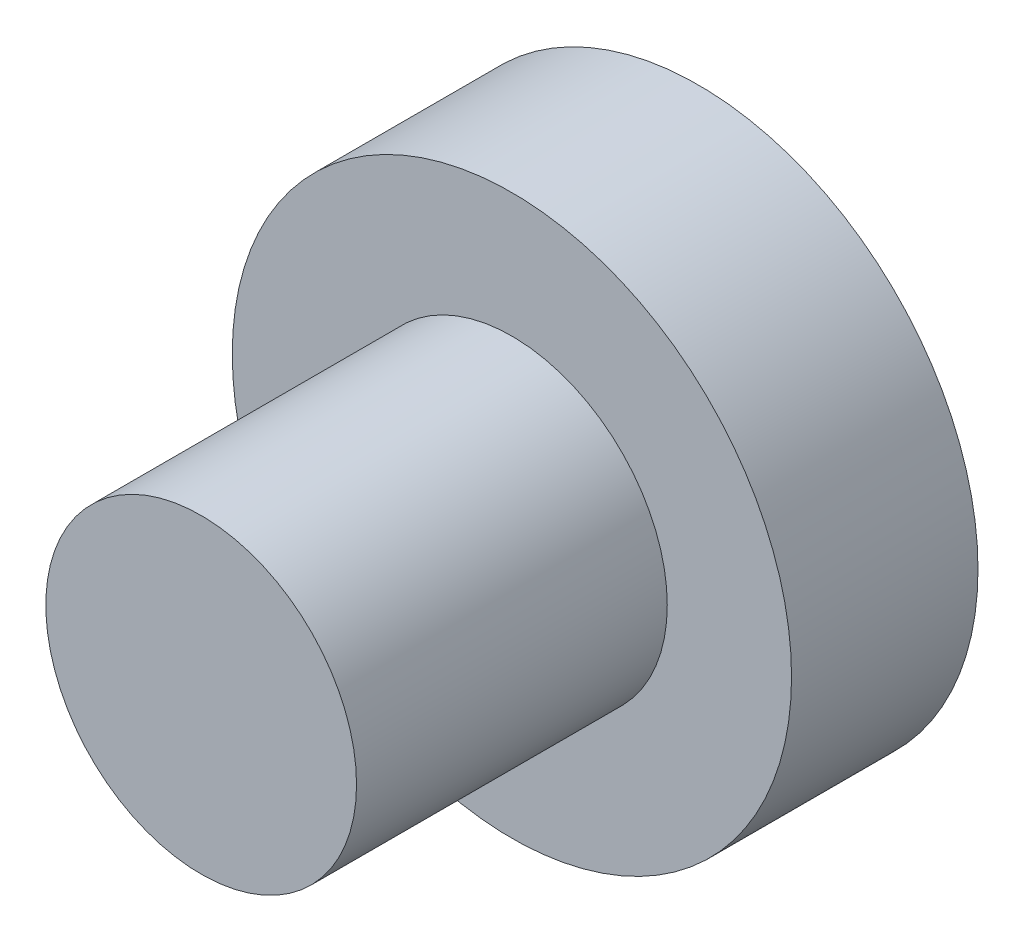
SolidWorks part; units mm, degrees
ref_plane "Front Plane" through (0, 0, 0) normal (0, 0, 1) x (1, 0, 0)
ref_plane "Top Plane" through (0, 0, 0) normal (0, 1, 0) x (1, 0, 0)
ref_plane "Right Plane" through (0, 0, 0) normal (1, 0, 0) x (0, 0, -1)
sketch "Sketch2" plane through (0, 0, 0) normal (0, 0, 1) x (1, 0, 0)
  circle A0 centre (0, 0) radius 2.5
  circle A1 centre (0, 0) radius 4.5
  dimension "D1" = 5
  dimension "D2" = 9
extrude "Boss-Extrude1" add sketch "Sketch2" along normal blind 3
sketch "Sketch3" plane through (0, 0, 3) normal (0, 0, 1) x (1, 0, 0)
  circle A0 centre (0, 0) radius 2.5
extrude "Boss-Extrude2" add sketch "Sketch3" along normal blind 5 separate body
sketch "Sketch4" plane through (0, 0, 8) normal (0, 0, 1) x (1, 0, 0)
  circle A0 centre (0, 0) radius 3.5
  dimension "D1" = 7
